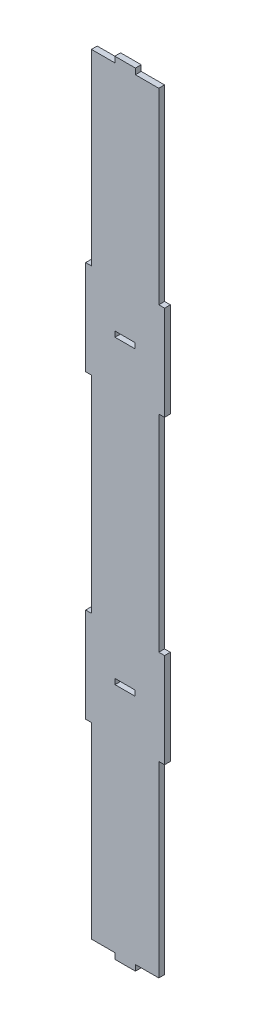
SolidWorks part; units mm, degrees
ref_plane "Front Plane" through (0, 0, 0) normal (0, 0, 1) x (1, 0, 0)
ref_plane "Top Plane" through (0, 0, 0) normal (0, 1, 0) x (1, 0, 0)
ref_plane "Right Plane" through (0, 0, 0) normal (1, 0, 0) x (0, 0, -1)
sketch "Sketch2" plane through (0, 0, 0) normal (0, 0, 1) x (1, 0, 0)
  line L0 (0, 286) -> (0, -286) construction
  line L1 (-25, -286) -> (-7.65, -286)
  line L2 (-25, -286) -> (-25, -146.7666)
  line L3 (-25, 286) -> (-7.65, 286)
  line L4 (25, -286) -> (25, -146.7666)
  line L5 (-25, -286) -> (25, 286) construction
  line L6 (-25, 286) -> (25, -286) construction
  line L7 (25, 0) -> (-25, 0) construction
  line L8 (-25, 146.7667) -> (-25, 286)
  line L9 (-25, 146.7667) -> (-29.3, 146.7667)
  line L11 (-25, 76.5667) -> (-29.3, 76.5667)
  line L12 (-29.3, 146.7667) -> (-29.3, 76.5667)
  line L13 (-25, -76.5666) -> (-25, 76.5667)
  line L14 (-25, -76.5666) -> (-29.3, -76.5666)
  line L16 (-25, -146.7666) -> (-29.3, -146.7666)
  line L17 (-29.3, -76.5666) -> (-29.3, -146.7666)
  line L18 (29.3, -76.5666) -> (29.3, -146.7666)
  line L19 (25, -146.7666) -> (29.3, -146.7666)
  line L20 (25, -76.5666) -> (29.3, -76.5666)
  line L21 (29.3, 146.7667) -> (29.3, 76.5667)
  line L22 (25, 76.5667) -> (29.3, 76.5667)
  line L23 (25, 146.7667) -> (29.3, 146.7667)
  line L24 (25, 146.7667) -> (25, 286)
  line L25 (25, -76.5666) -> (25, 76.5667)
  line L26 (7.65, 286) -> (25, 286)
  line L28 (-7.65, 286) -> (-7.65, 290.3)
  line L29 (-7.65, 290.3) -> (7.65, 290.3)
  line L30 (7.65, 286) -> (7.65, 290.3)
  line L31 (7.65, -286) -> (25, -286)
  line L33 (-7.65, -286) -> (-7.65, -290.3)
  line L34 (-7.65, -290.3) -> (7.65, -290.3)
  line L35 (7.65, -286) -> (7.65, -290.3)
  line L36 (7.5, 109.6666) -> (-7.5, 109.6666)
  line L37 (7.5, -113.6666) -> (-7.5, -113.6666)
  line L38 (7.5, -113.6666) -> (7.5, -109.6666)
  line L39 (7.5, -109.6666) -> (-7.5, -109.6666)
  line L40 (-7.5, -113.6666) -> (-7.5, -109.6666)
  line L41 (7.5, -113.6666) -> (-7.5, -109.6666) construction
  line L42 (7.5, -109.6666) -> (-7.5, -113.6666) construction
  line L43 (-7.5, 113.6666) -> (-7.5, 109.6666)
  line L44 (7.5, 113.6666) -> (-7.5, 113.6666)
  line L45 (7.5, 113.6666) -> (7.5, 109.6666)
  point P0 (0, 0)
  point P7 (0, -111.6666)
  point P14 (-29.3, 111.6667)
  point P20 (-29.3, -111.6666)
  point P32 (0, 290.3)
  point P38 (0, -290.3)
  dimension "D1" = 572
  dimension "D2" = 50
  dimension "D3" = 4.3
  dimension "D4" = 70.2
  dimension "D5" = 174.3333
  dimension "D6" = 223.3333
  dimension "D7" = 174.3334
  dimension "D8" = 4.3
  dimension "D9" = 15.3
  dimension "D10" = 15.3
  dimension "D11" = 4.3
  dimension "D12" = 4
  dimension "D13" = 15
extrude "Boss-Extrude1" add sketch "Sketch2" along normal blind 4.3
equation "\"4ز3\"=5.6211"
